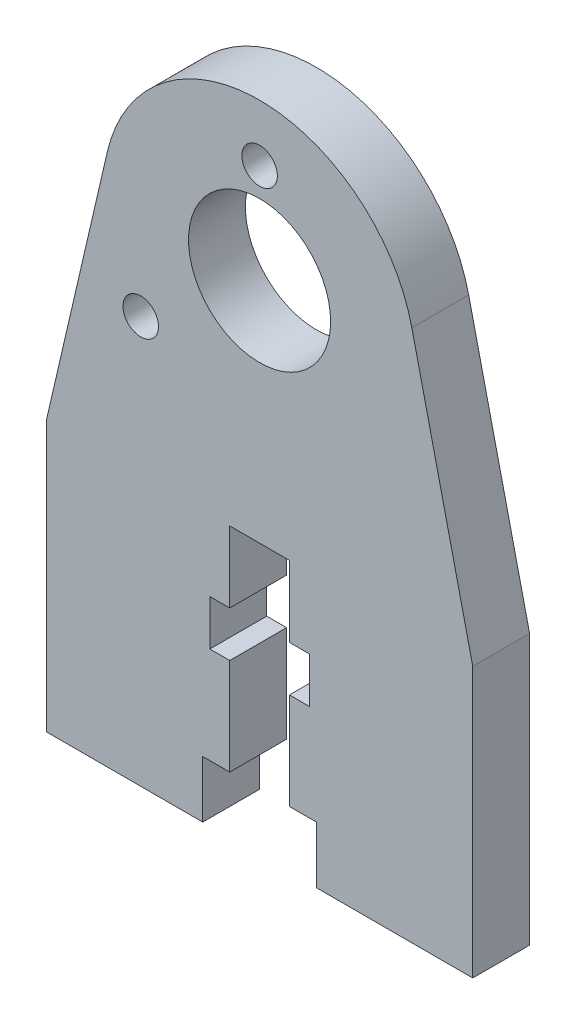
SolidWorks part; units mm, degrees
ref_plane "Front Plane" through (0, 0, 0) normal (0, 0, 1) x (1, 0, 0)
ref_plane "Top Plane" through (0, 0, 0) normal (0, 1, 0) x (1, 0, 0)
ref_plane "Right Plane" through (0, 0, 0) normal (1, 0, 0) x (0, 0, -1)
sketch "Sketch6" plane through (0, 0, 0) normal (0, 0, 1) x (1, 0, 0)
  line L0 (0, 0) -> (0, 35) construction
  line L1 (15, 0) -> (15, 15)
  line L2 (15, 15) -> (10.7159, 33.4837)
  line L4 (-15, 15) -> (-10.7159, 33.4837)
  line L5 (-15, 0) -> (-15, 15)
  line L6 (15, 0) -> (15, -4)
  line L7 (15, -4) -> (4, -4)
  line L8 (4, -4) -> (4, 0)
  line L9 (4, 0) -> (-4, 0)
  line L10 (-4, -4) -> (-4, 0)
  line L11 (-15, -4) -> (-4, -4)
  line L12 (-15, 0) -> (-15, -4)
  arc A0 (-10.7159, 33.4837) -> (10.7159, 33.4837) centre (0, 31) cw
  circle A1 centre (0, 31) radius 5
  dimension "D2" = 10
  dimension "D3" = 11
  dimension "D1" = 4
  dimension "D4" = 15
  dimension "D5" = 30
  dimension "D6" = 4
  dimension "D7" = 35
extrude "Boss-Extrude5" add sketch "Sketch6" along normal blind 4
sketch "Sketch10" plane through (0, 0, 0) normal (0, 0, -1) x (-1, 0, 0)
  circle A0 centre (0, 38) radius 1.25
  circle A1 centre (0, 31) radius 5 construction
  circle A3 centre (4.9497, 44.9497) radius 1.25
  circle A4 centre (13.364, 46.364) radius 1.25
  circle A5 centre (20.3137, 41.4142) radius 1.25
  circle A6 centre (21.7279, 33) radius 1.25
  circle A7 centre (16.7782, 26.0503) radius 1.25
  circle A8 centre (8.364, 24.636) radius 1.25
  circle A9 centre (1.4142, 29.5858) radius 1.25
  dimension "D1" = 2.5
  dimension "D2" = 7
  dimension "D3" = 8
extrude "Cut-Extrude6" cut sketch "Sketch10" against normal through all
sketch "Sketch11" plane through (0, 0, 4) normal (0, 0, 1) x (1, 0, 0)
  line L0 (0, 0) -> (0, 47) construction
  line L1 (4, 0) -> (-4, 0) construction
  line L2 (-2.1, 10) -> (-2.1, 15)
  line L3 (-3.5, 10) -> (-2.1, 10)
  line L4 (2.1, 0) -> (2.1, 6.8)
  line L5 (2.1, 6.8) -> (3.5, 6.8)
  line L6 (3.5, 6.8) -> (3.5, 10)
  line L7 (3.5, 10) -> (2.1, 10)
  line L8 (2.1, 10) -> (2.1, 15)
  line L9 (2.1, 15) -> (-2.1, 15)
  line L10 (-3.5, 6.8) -> (-3.5, 10)
  line L11 (-2.1, 6.8) -> (-3.5, 6.8)
  line L12 (-2.1, 0) -> (-2.1, 6.8)
  line L13 (-2.1, 0) -> (2.1, 0)
  point P8 (0, 15)
  point P20 (21.8009, 10.0281)
  dimension "D1" = 7
  dimension "D2" = 4.2
  dimension "D3" = 15
  dimension "D4" = 3.2
  dimension "D5" = 5
extrude "Cut-Extrude7" cut sketch "Sketch11" against normal through all
